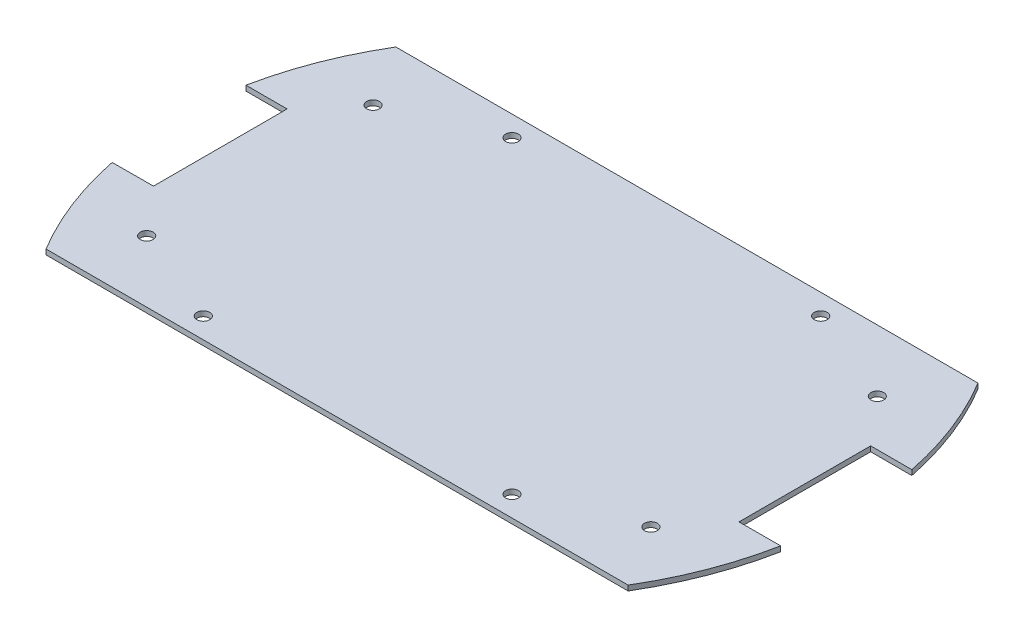
SolidWorks part; units mm, degrees
ref_plane "前基準面" through (0, 0, 0) normal (0, 0, 1) x (1, 0, 0)
ref_plane "上基準面" through (0, 0, 0) normal (0, 1, 0) x (1, 0, 0)
ref_plane "右基準面" through (0, 0, 0) normal (1, 0, 0) x (0, 0, -1)
sketch "草圖7" plane through (0, 0, 0) normal (0, 1, 0) x (1, 0, 0)
  line L1 (-34, 34) -> (34, 34)
  line L2 (-34, 34) -> (-34, -34)
  line L3 (-34, -34) -> (34, -34)
  line L4 (34, 34) -> (34, -34)
  line L5 (-34, 34) -> (34, -34) construction
  line L6 (-34, -34) -> (34, 34) construction
  point P0 (0, 0)
  point P7 (-30, 30)
  point P10 (30, 30)
  point P11 (30, -30)
  point P12 (-30, -30)
  point P13 (0, 0)
  dimension "D1" = 68
  dimension "D2" = 4
  dimension "D3" = 4
sketch "草圖10" plane through (0, 0, 0) normal (0, 1, 0) x (1, 0, 0)
  line L0 (-56.5685, 34) -> (56.5685, 34)
  line L1 (-34, 34) -> (34, 34) construction
  line L2 (-56.5685, -34) -> (56.5685, -34)
  line L3 (-34, -34) -> (34, -34) construction
  line L4 (-34, 34) -> (-34, -34) construction
  line L5 (0, 0) -> (0, 19.0172) construction
  line L6 (0, 0) -> (-12.2861, 0) construction
  line L7 (-56.707, 13) -> (-56.707, -13)
  line L8 (-64.707, 13) -> (64.707, 13)
  line L9 (56.707, 13) -> (56.707, -13)
  line L10 (-64.707, -13) -> (64.7924, -12.5675)
  arc A0 (-64.707, -13) -> (-56.5685, -34) centre (0, 0) ccw
  arc A3 (-56.5685, 34) -> (-64.707, 13) centre (0, 0) ccw
  arc A4 (64.707, 13) -> (56.5685, 34) centre (0, 0) ccw
  arc A5 (56.5685, -34) -> (64.7924, -12.5675) centre (0, 0) ccw
  point P12 (-49, 22)
  point P24 (56.707, 0)
  point P27 (-56.707, 0)
  dimension "D1" = 8
  dimension "D2" = 13
  dimension "D4" = 15
  dimension "D5" = 12
extrude "填料-伸長2" add sketch "草圖10" along normal blind 1
hole_wizard "M3x0.5  螺絲攻的螺孔鑽1" positions "3D草圖2" profile "草圖13" hole size "M3x0.5" standard "JIS"
sketch3d "3D草圖2"
  point P0 (-30, 0, -30)
  point P3 (-30, 1, -30)
  point P5 (-30, 1, 30)
  point P11 (30, 1, -30)
  point P13 (30, 1, 30)
sketch "草圖13" plane through (30, 1, 30) normal (1, 0, 0) x (0, 0, 1)
  line L0 (0, 0) -> (0, 4.7511)
  line L1 (0, 4.7511) -> (1.25, 4)
  line L2 (1.25, 4) -> (1.25, 0)
  line L5 (1.25, 0) -> (0, 0)
  line L10 (0, 4.7511) -> (-1.25, 4) construction
  line L11 (0, -6.35) -> (0, 107.95) construction
  dimension "鑽孔直徑" = 2.5
  dimension "鑽孔深度" = 4
  dimension "導頭角度" = 118
hole_wizard "M3x0.5  螺絲攻的螺孔鑽2" positions "3D草圖3" profile "草圖14" hole size "M3x0.5" standard "JIS"
sketch3d "3D草圖3"
  point P0 (-49, 1, -22)
sketch "草圖14" plane through (-49, 1, -22) normal (1, 0, 0) x (0, 0, 1)
  line L0 (0, 0) -> (0, 4.7511)
  line L1 (0, 4.7511) -> (1.25, 4)
  line L2 (1.25, 4) -> (1.25, 0)
  line L5 (1.25, 0) -> (0, 0)
  line L10 (0, 4.7511) -> (-1.25, 4) construction
  line L11 (0, -6.35) -> (0, 107.95) construction
  dimension "鑽孔直徑" = 2.5
  dimension "鑽孔深度" = 4
  dimension "導頭角度" = 118
pattern_linear "直線複製排列1" count 2 spacing 98 along (1, 0, 0) count 2 spacing 44 along (0, 0, 1) of "M3x0.5  螺絲攻的螺孔鑽2"
